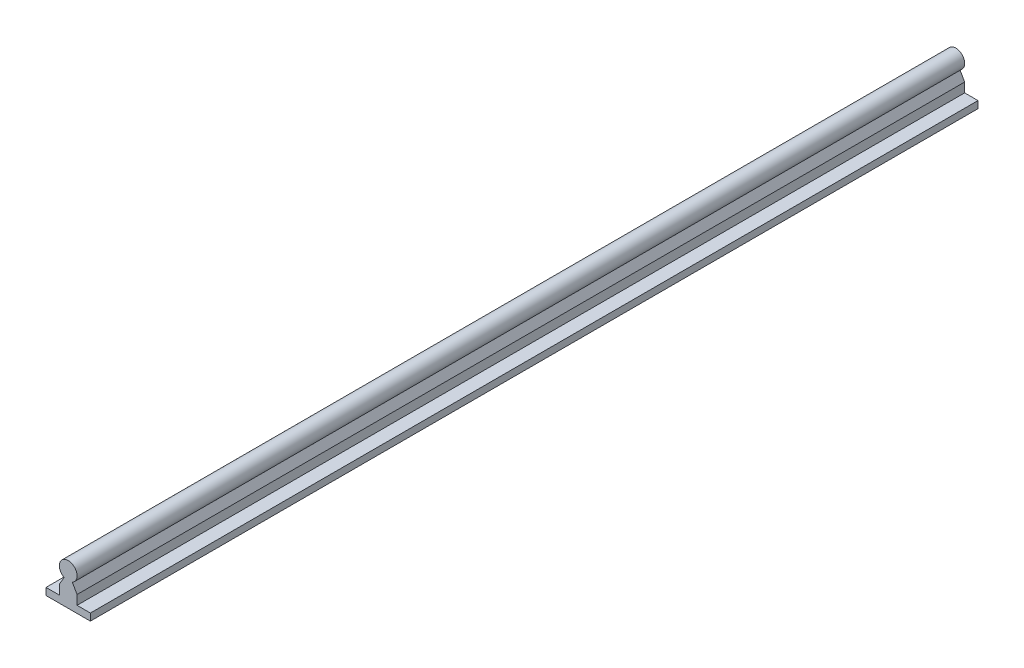
SolidWorks part; units mm, degrees
ref_plane "Front Plane" through (0, 0, 0) normal (0, 0, 1) x (1, 0, 0)
ref_plane "Top Plane" through (0, 0, 0) normal (0, 1, 0) x (1, 0, 0)
ref_plane "Right Plane" through (0, 0, 0) normal (1, 0, 0) x (0, 0, -1)
sketch "Sketch1" plane through (0, 0, 0) normal (0, 0, 1) x (1, 0, 0)
  line L0 (0, 0) -> (0, 22) construction
  line L1 (15, 0) -> (-15, 0)
  line L2 (-15, 0) -> (-15, 4.7625)
  line L3 (-15, 4.7625) -> (-6, 4.7625)
  line L4 (-6, 4.7625) -> (-6, 11.1125)
  line L5 (-6, 11.1125) -> (-2.783, 16.6845)
  line L6 (0, 22) -> (0, 28) construction
  line L7 (6, 11.1125) -> (2.783, 16.6845)
  line L8 (6, 4.7625) -> (6, 11.1125)
  line L9 (15, 4.7625) -> (6, 4.7625)
  line L10 (15, 0) -> (15, 4.7625)
  arc A0 (2.783, 16.6845) -> (-2.783, 16.6845) centre (0, 22) ccw
  point P14 (0, 0)
  dimension "D3" = 6
  dimension "D1" = 28
  dimension "D2" = 15
  dimension "D4" = 4.7625
  dimension "D5" = 6.35
  dimension "D6" = 30
extrude "Boss-Extrude1" add sketch "Sketch1" along normal blind 600
